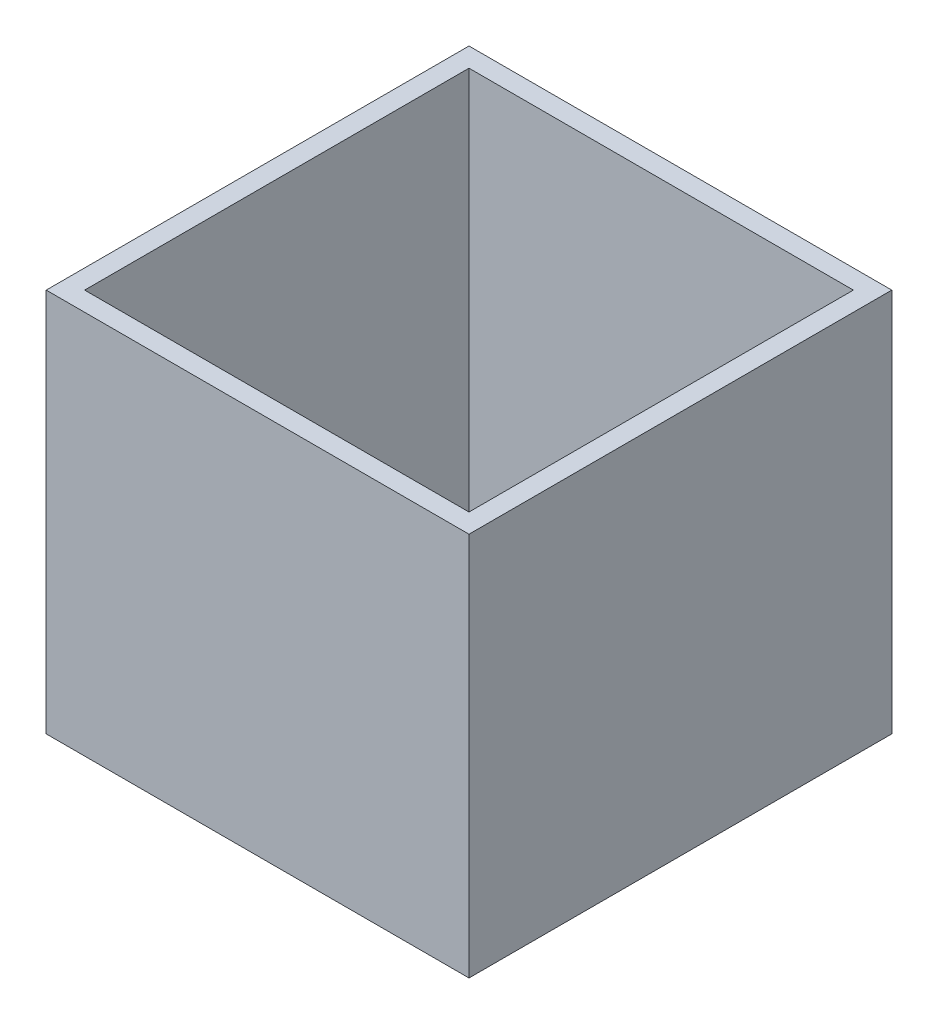
SolidWorks part; units mm, degrees
ref_plane "Front Plane" through (0, 0, 0) normal (0, 0, 1) x (1, 0, 0)
ref_plane "Top Plane" through (0, 0, 0) normal (0, 1, 0) x (1, 0, 0)
ref_plane "Right Plane" through (0, 0, 0) normal (1, 0, 0) x (0, 0, -1)
sketch "Sketch2" plane through (0, 0, 0) normal (0, 1, 0) x (1, 0, 0)
  line L1 (-38.1, 38.1) -> (38.1, 38.1)
  line L2 (-38.1, 38.1) -> (-38.1, -38.1)
  line L3 (-38.1, -38.1) -> (38.1, -38.1)
  line L4 (38.1, 38.1) -> (38.1, -38.1)
  line L5 (-38.1, 38.1) -> (38.1, -38.1) construction
  line L6 (-38.1, -38.1) -> (38.1, 38.1) construction
  point P0 (0, 0)
  dimension "D1" = 76.2
  dimension "D2" = 76.2
extrude "Boss-Extrude2" add sketch "Sketch2" along normal blind 76.2
shell "Shell1" thickness 3.81
